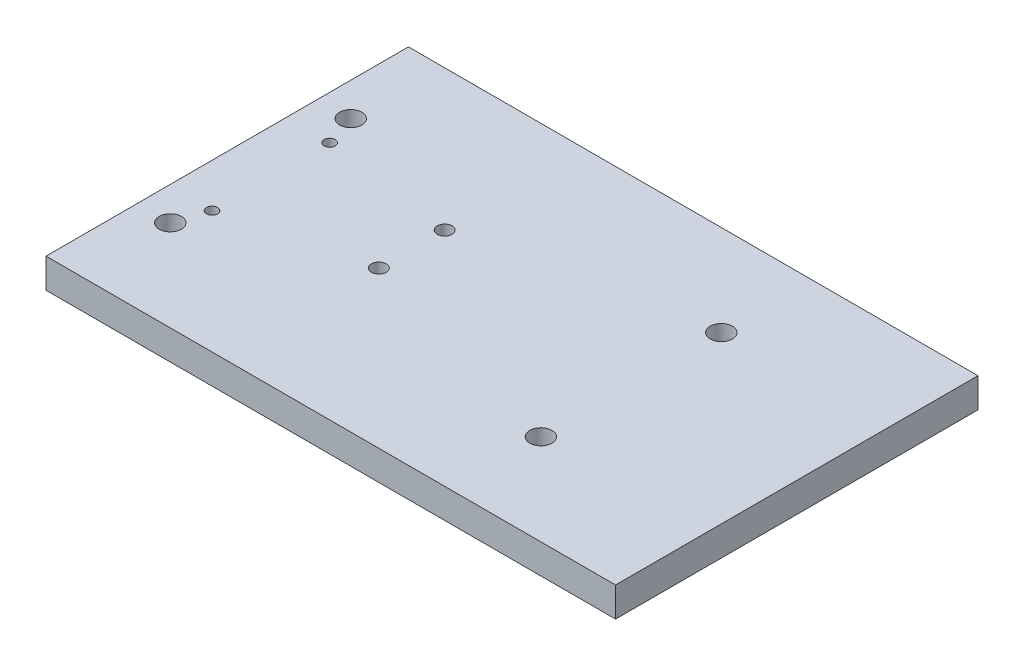
SolidWorks part; units mm, degrees
ref_plane "Front Plane" through (0, 0, 0) normal (0, 0, 1) x (1, 0, 0)
ref_plane "Top Plane" through (0, 0, 0) normal (0, 1, 0) x (1, 0, 0)
ref_plane "Right Plane" through (0, 0, 0) normal (1, 0, 0) x (0, 0, -1)
sketch "草图1" plane through (0, 0, 0) normal (0, 1, 0) x (1, 0, 0)
  line L1 (-38.5, 24.5) -> (38.5, 24.5)
  line L2 (-38.5, 24.5) -> (-38.5, -24.5)
  line L3 (-38.5, -24.5) -> (38.5, -24.5)
  line L4 (38.5, 24.5) -> (38.5, -24.5)
  line L5 (-38.5, 24.5) -> (38.5, -24.5) construction
  line L6 (-38.5, -24.5) -> (38.5, 24.5) construction
  point P0 (0, 0)
  dimension "D1" = 77
  dimension "D2" = 49
extrude "凸台-拉伸1" add sketch "草图1" along normal blind 4
sketch "草图2" plane through (0, 4, 0) normal (0, 1, 0) x (1, 0, 0)
  line L0 (-38.5, -24.5) -> (38.5, -24.5) construction
  line L1 (-38.5, 24.5) -> (-38.5, -24.5) construction
  circle A0 centre (-34, -12.2) radius 1.5
  circle A1 centre (16.1, -12.2) radius 1.5
  circle A2 centre (16.1, 12.2) radius 1.5
  circle A3 centre (-34, 12.2) radius 1.5
  circle A4 centre (-32.6, 7.95) radius 0.75
  circle A5 centre (-32.6, -7.95) radius 0.75
  circle A6 centre (-14.6, -3.4) radius 1
  circle A7 centre (-14.6, 5.5) radius 1
  dimension "D1" = 3
  dimension "D6" = 1.5
  dimension "D7" = 1.5
  dimension "D12" = 2
  dimension "D13" = 2
  dimension "D4" = 12.3
  dimension "D5" = 4.5
  dimension "D8" = 4.25
  dimension "D9" = 4.25
  dimension "D10" = 1.4
  dimension "D11" = 1.4
  dimension "D14" = 8.9
  dimension "D15" = 19.4
  dimension "D16" = 6.7
  dimension "D2" = 2
  dimension "D3" = 2
extrude "切除-拉伸2" cut sketch "草图2" against normal blind 4
